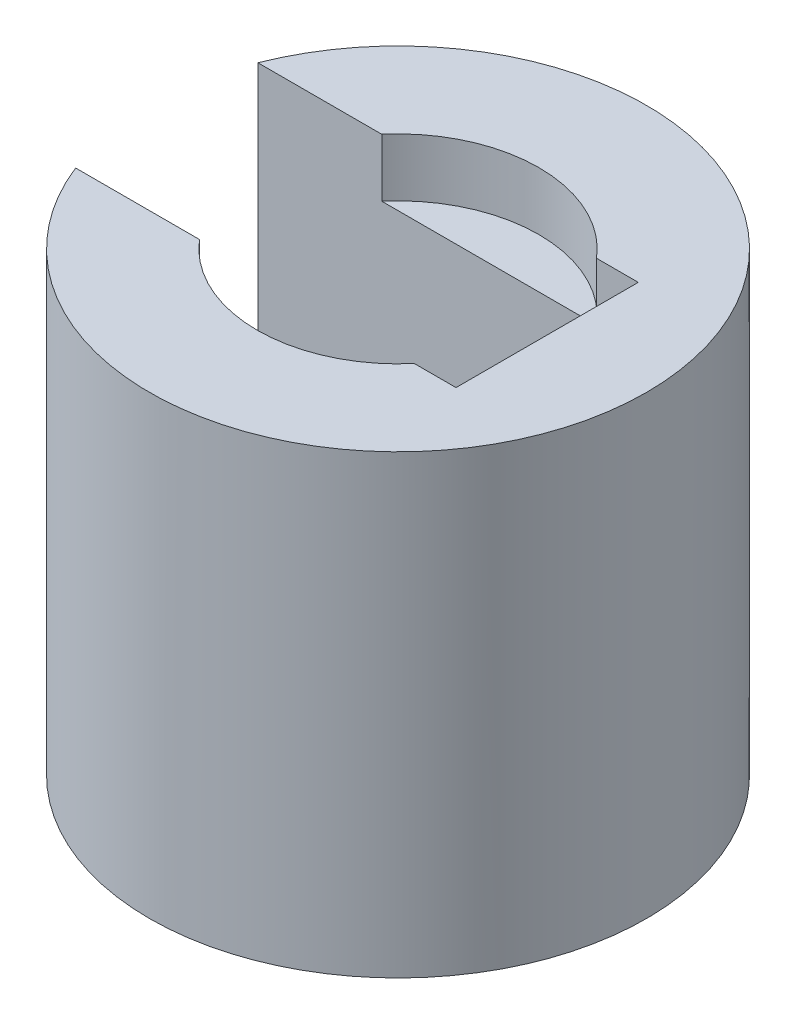
SolidWorks part; units mm, degrees
ref_plane "Front Plane" through (0, 0, 0) normal (0, 0, 1) x (1, 0, 0)
ref_plane "Top Plane" through (0, 0, 0) normal (0, 1, 0) x (1, 0, 0)
ref_plane "Right Plane" through (0, 0, 0) normal (1, 0, 0) x (0, 0, -1)
sketch "Sketch1" plane through (0, 0, 0) normal (0, 1, 0) x (1, 0, 0)
  circle A0 centre (0, 0) radius 30
  dimension "D1" = 60
extrude "Boss-Extrude1" add sketch "Sketch1" along normal blind 55 contours A0
sketch "Sketch3" plane through (0, 55, 0) normal (0, 1, 0) x (1, 0, 0)
  circle A0 centre (0, 0) radius 17
  dimension "D1" = 34
extrude "hub pocket" cut sketch "Sketch3" against normal blind 7
sketch "Sketch2" plane through (0, 55, 0) normal (0, 1, 0) x (1, 0, 0)
  line L0 (18, 0) -> (0, 0) construction
  line L1 (-35.9842, 11) -> (18, 11)
  line L2 (-35.9842, 11) -> (-35.9842, -11)
  line L3 (-35.9842, -11) -> (18, -11)
  line L4 (18, 11) -> (18, -11)
  dimension "D1" = 22
  dimension "D2" = 18
extrude "servo pocket" cut sketch "Sketch2" against normal blind 50 contours L1 L4 L3 L2
sketch "Sketch4" plane through (0, 0, 0) normal (0, 0, 1) x (1, 0, 0)
  line L0 (18, 32.5) -> (11, 32.5)
  line L1 (18, 5) -> (18, 55) construction
  line L2 (11, 32.5) -> (11, 27.5)
  line L3 (11, 27.5) -> (18, 15.3756)
  line L4 (18, 15.3756) -> (18, 32.5)
  line L5 (30, 55) -> (-27.9106, 55) construction
  point P4 (18, 25.1187)
  dimension "D1" = 30
  dimension "D2" = 7
  dimension "D3" = 5
  dimension "D4" = 22.5
extrude "Servo front mount" add sketch "Sketch4" against normal up to surface and the other way up to surface up to face at (-2.4776, 40.75, -11) other way up to face at (-2.4776, 40.75, 11)
sketch "Sketch5" plane through (0, 0, 0) normal (0, 0, 1) x (1, 0, 0)
  line L0 (18, 15.3756) -> (23.9904, 5)
  line L1 (23.9904, 5) -> (18, 5)
  line L2 (18, 5) -> (18, 15.3756) construction
  line L3 (18, 5) -> (18, 15.3756)
  line L4 (-27.9106, 5) -> (-30, 5) construction
  line L5 (18, 15.3756) -> (11, 27.5) construction
  point P3 (18, 4.919)
  point P7 (0, 0)
  point P8 (24.0285, 6.1156)
  point P9 (0, 0)
extrude "Wire access" cut sketch "Sketch5" against normal mid plane 22
